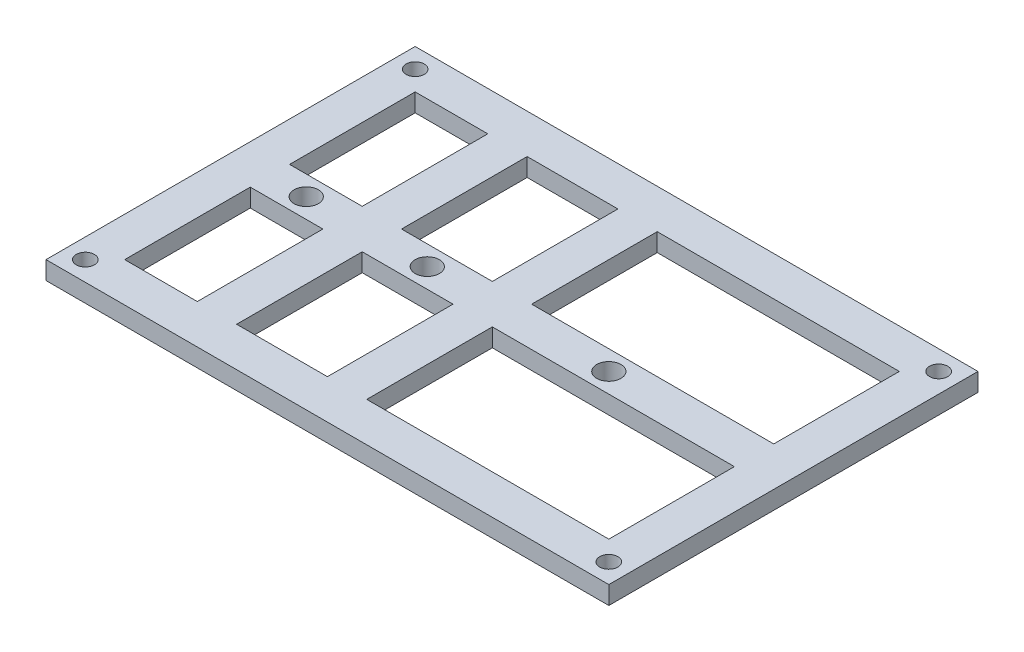
SolidWorks part; units mm, degrees
ref_plane "Front Plane" through (0, 0, 0) normal (0, 0, 1) x (1, 0, 0)
ref_plane "Top Plane" through (0, 0, 0) normal (0, 1, 0) x (1, 0, 0)
ref_plane "Right Plane" through (0, 0, 0) normal (1, 0, 0) x (0, 0, -1)
sketch "Sketch1" plane through (0, 0, 0) normal (0, 1, 0) x (1, 0, 0)
  line L21 (-46.5, -30.5) -> (-46.5, 30.5)
  line L25 (-40, -24) -> (-28, -24)
  line L26 (-40, -24) -> (-40, -3.25)
  line L27 (-40, 24) -> (-28, 24)
  line L28 (40, -24) -> (40, -3.25)
  line L29 (-40, -24) -> (40, 24) construction
  line L30 (-40, 24) -> (40, -24) construction
  line L31 (-46.5, 30.5) -> (46.5, 30.5)
  line L32 (46.5, -30.5) -> (46.5, 30.5)
  line L33 (-46.5, -30.5) -> (46.5, -30.5)
  line L34 (-28, 24) -> (-28, 3.25)
  line L35 (-21.5, 24) -> (-21.5, 3.25)
  line L36 (-6.5, 24) -> (-6.5, 3.25)
  line L37 (0, 24) -> (0, 3.25)
  line L38 (-40, 3.25) -> (-28, 3.25)
  line L39 (-40, -3.25) -> (-28, -3.25)
  line L40 (-28, -3.25) -> (-28, -24)
  line L41 (-21.5, -3.25) -> (-21.5, -24)
  line L42 (-21.5, 3.25) -> (-6.5, 3.25)
  line L43 (-21.5, -3.25) -> (-6.5, -3.25)
  line L44 (0, -3.25) -> (40, -3.25)
  line L45 (0, 3.25) -> (40, 3.25)
  line L46 (-6.5, -3.25) -> (-6.5, -24)
  line L47 (0, -3.25) -> (0, -24)
  line L48 (24.4353, 0) -> (-42.7672, 0) construction
  line L49 (-21.5, 24) -> (-6.5, 24)
  line L50 (-40, 24) -> (40, 24) construction
  line L51 (0, 24) -> (40, 24)
  line L52 (40, 3.25) -> (40, 24)
  line L53 (40, -24) -> (40, 24) construction
  line L54 (-40, 3.25) -> (-40, 24)
  line L55 (-40, -24) -> (-40, 24) construction
  line L56 (-21.5, -24) -> (-6.5, -24)
  line L57 (-40, -24) -> (40, -24) construction
  line L58 (0, -24) -> (40, -24)
  line L59 (-40, -24) -> (-46.5, -30.5) construction
  line L60 (40, -24) -> (46.5, -30.5) construction
  line L61 (-34, 3.25) -> (-34, -3.25) construction
  line L62 (-14, 3.25) -> (-14, -3.25) construction
  line L63 (20, 3.25) -> (20, -3.25) construction
  circle A0 centre (-34, 0) radius 2
  circle A1 centre (-14, 0) radius 2
  circle A2 centre (16, 0) radius 2
  circle A3 centre (43.25, -27.25) radius 1.5
  circle A5 centre (-43.25, -27.25) radius 1.5
  circle A6 centre (43.25, 27.25) radius 1.5
  circle A7 centre (-43.25, 27.25) radius 1.5
  point P0 (0, 0)
  point P44 (43.25, -27.25)
  point P46 (-43.25, -27.25)
  point P54 (0, 0)
  point P55 (0, 0)
  dimension "D5" = 4
  dimension "D10" = 24
  dimension "D11" = 3
  dimension "D1" = 6.5
  dimension "D2" = 6.5
  dimension "D3" = 6.5
  dimension "D4" = 6.5
  dimension "D6" = 20
  dimension "D7" = 30
  dimension "D8" = 6
  dimension "D9" = 24
extrude "Boss-Extrude1" add sketch "Sketch1" along normal mid plane 3
